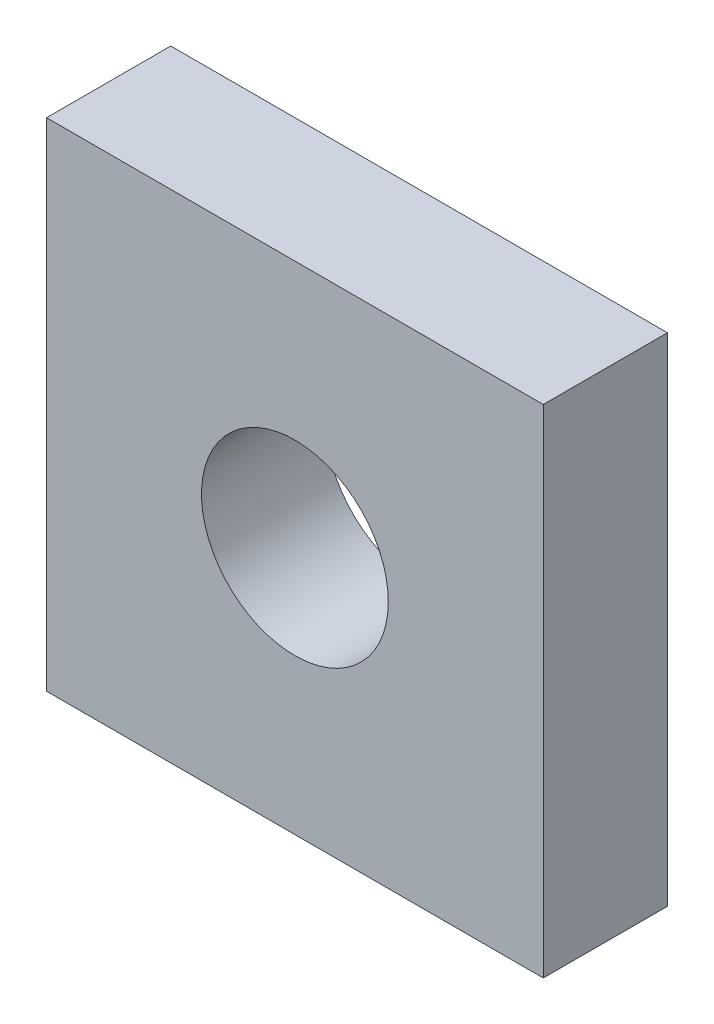
SolidWorks part; units mm, degrees
ref_plane "Front Plane" through (0, 0, 0) normal (0, 0, 1) x (1, 0, 0)
ref_plane "Top Plane" through (0, 0, 0) normal (0, 1, 0) x (1, 0, 0)
ref_plane "Right Plane" through (0, 0, 0) normal (1, 0, 0) x (0, 0, -1)
sketch "Sketch1" plane through (0, 0, 0) normal (0, 0, 1) x (1, 0, 0)
  line L13 (-12.8607, 19.5414) -> (12.5393, 19.5414)
  line L14 (-12.8607, 19.5414) -> (-12.8607, -5.8586)
  line L16 (12.5393, 19.5414) -> (12.5393, -5.8586)
  line L17 (-12.8607, 19.5414) -> (12.5393, -5.8586) construction
  line L18 (-12.8607, -5.8586) -> (12.5393, 19.5414) construction
  line L21 (-12.8607, -5.8586) -> (12.5393, -5.8586)
  circle A0 centre (-0.1607, 6.8414) radius 4.7752
  dimension "D1" = 9.5504
  dimension "D2" = 25.4
  dimension "D3" = 25.4
extrude "Boss-Extrude1" add sketch "Sketch1" along normal blind 6.35
